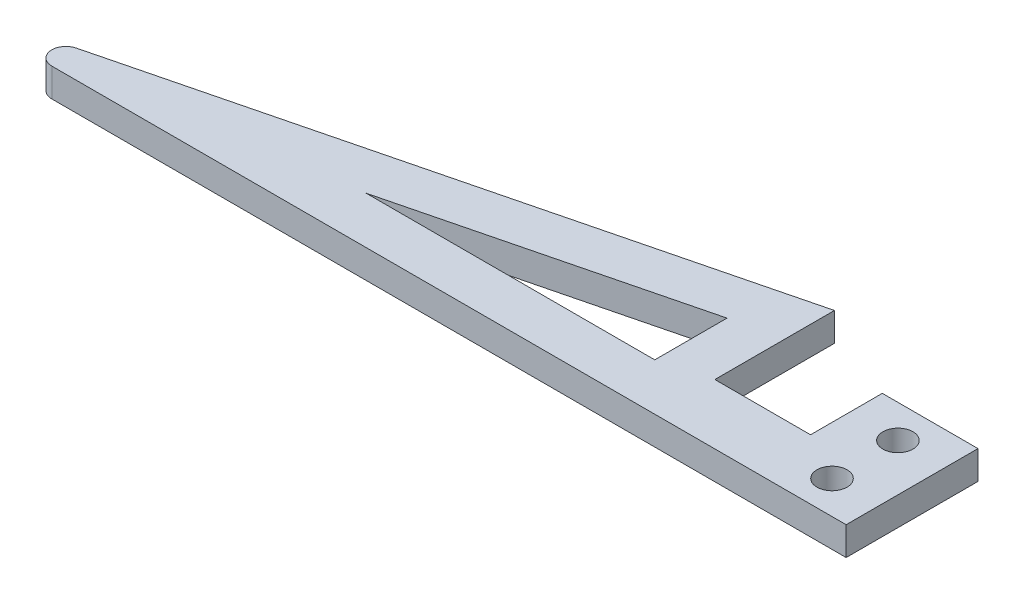
SolidWorks part; units mm, degrees
material "Ti-5Al-2.5Sn Annealed (SS)"
ref_plane "Front Plane" through (0, 0, 0) normal (0, 0, 1) x (1, 0, 0)
ref_plane "Top Plane" through (0, 0, 0) normal (0, 1, 0) x (1, 0, 0)
ref_plane "Right Plane" through (0, 0, 0) normal (1, 0, 0) x (0, 0, -1)
sketch "Sketch2" plane through (0, 0, 0) normal (0, 1, 0) x (1, 0, 0)
  line L1 (0, -6.35) -> (-96.5, -6.35)
  line L6 (-20.32, 0.03) -> (-10.16, 0.03)
  line L7 (-20.32, 0.03) -> (-20.32, 12.73)
  line L9 (-20.32, 12.73) -> (-96.5, -6.35)
  line L17 (-25.32, -1.35) -> (-25.32, 6.3233)
  line L18 (-25.32, 6.3233) -> (-55.9567, -1.35)
  line L20 (0, -6.35) -> (0, 7.65)
  line L21 (0, 7.65) -> (-10.16, 7.65)
  line L22 (-10.16, 7.65) -> (-10.16, 0.03)
  line L23 (-25.32, 0.03) -> (-25.32, 6.3233) construction
  line L24 (-25.32, -1.35) -> (-55.9567, -1.35)
  line L25 (0, -1.35) -> (-55.9567, -1.35) construction
  circle A0 centre (-5, -2.85) radius 1.6
  circle A1 centre (-5, 4.15) radius 1.6
  point P22 (0, 0)
  dimension "D4" = 5
  dimension "D6" = 7
  dimension "D1" = 14
  dimension "D2" = 10.16
  dimension "D3" = 7.62
  dimension "D5" = 3.5
  dimension "D7" = 96.5
  dimension "D8" = 12.7
  dimension "D9" = 5
extrude "Boss-Extrude1" add sketch "Sketch2" along normal blind 3.0226
fillet "Fillet1" radius 1.5 1 edges at (-96.5, 1.5113, 6.35)
